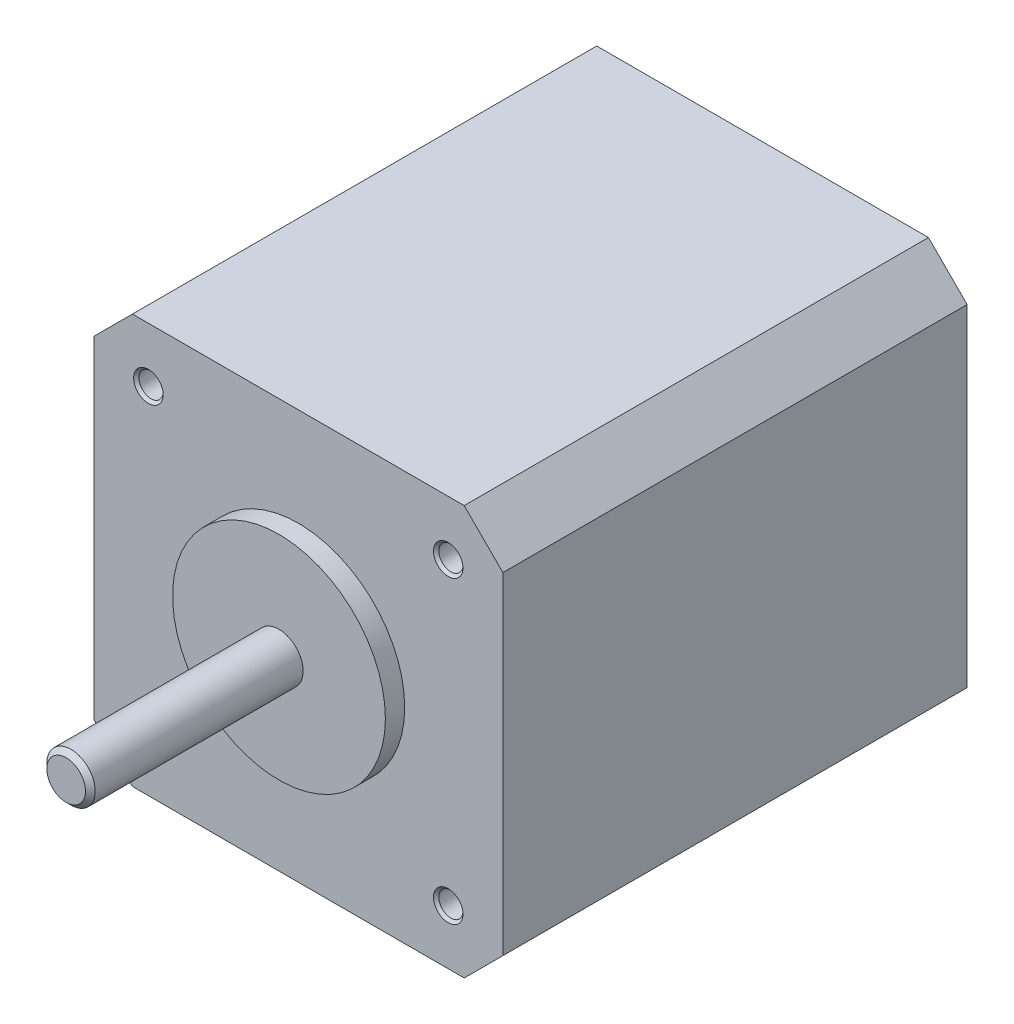
SolidWorks part; units mm, degrees
ref_plane "Front" through (0, 0, 0) normal (0, 0, 1) x (1, 0, 0)
ref_plane "Top" through (0, 0, 0) normal (0, 1, 0) x (1, 0, 0)
ref_plane "Right" through (0, 0, 0) normal (1, 0, 0) x (0, 0, -1)
sketch "Sketch1" plane through (0, 0, 0) normal (0, 0, 1) x (1, 0, 0)
  line L0 (0, 21.15) -> (0, 0) construction
  line L1 (-21.15, 21.15) -> (21.15, 21.15)
  line L2 (-21.15, 21.15) -> (-21.15, -21.15)
  line L3 (-21.15, -21.15) -> (21.15, -21.15)
  line L4 (21.15, 21.15) -> (21.15, -21.15)
  line L5 (0, 0) -> (0, -21.15) construction
  line L7 (0, 0) -> (21.15, 0) construction
  dimension "D1" = 42.3
  dimension "D2" = 42.3
extrude "Boss-Extrude1" add sketch "Sketch1" along normal blind 48
sketch "Sketch2" plane through (0, 0, 48) normal (0, 0, 1) x (1, 0, 0)
  circle A0 centre (0, 0) radius 11
  dimension "D1" = 22
extrude "Boss-Extrude2" add sketch "Sketch2" along normal blind 2
sketch "Sketch3" plane through (0, 0, 50) normal (0, 0, 1) x (1, 0, 0)
  circle A0 centre (0, 0) radius 2.5
  dimension "D1" = 5
extrude "Boss-Extrude3" add sketch "Sketch3" along normal blind 22
chamfer "Chamfer1" distance 0.5 angle 45 1 edges at (2.5, 0, 72)
chamfer "Chamfer2" distance 4 angle 45 4 edges at (-21.15, -21.15, 24) (21.15, -21.15, 24) (-21.15, 21.15, 24) (21.15, 21.15, 24)
hole_wizard "M3 Tapped Hole1" positions "3DSketch1" profile "Sketch4" tap size "M3" standard "ISO"
sketch3d "3DSketch1"
  line L0 (-15.5, -15.5, 48) -> (-15.5, -21.15, 48) construction
  line L1 (-17.15, -21.15, 48) -> (17.15, -21.15, 48) construction
  line L3 (-15.5, -15.5, 48) -> (-21.15, -15.5, 48) construction
  line L4 (-21.15, 17.15, 48) -> (-21.15, -17.15, 48) construction
  line L6 (15.5, -15.5, 48) -> (15.5, -21.15, 48) construction
  line L8 (15.5, -15.5, 48) -> (21.15, -15.5, 48) construction
  line L9 (21.15, -17.15, 48) -> (21.15, 17.15, 48) construction
  line L11 (-15.5, 15.5, 48) -> (-15.5, 21.15, 48) construction
  line L12 (17.15, 21.15, 48) -> (-17.15, 21.15, 48) construction
  line L14 (-15.5, 15.5, 48) -> (-21.15, 15.5, 48) construction
  line L16 (15.5, 15.5, 48) -> (15.5, 21.15, 48) construction
  line L18 (15.5, 15.5, 48) -> (21.15, 15.5, 48) construction
  point P0 (-15.5, 15.5, 48)
  point P2 (15.5, 15.5, 48)
  point P4 (15.5, -15.5, 48)
  point P6 (-15.5, -15.5, 48)
  dimension "D1" = 31
sketch "Sketch4" plane through (-15.5, 15.5, 48) normal (1, 0, 0) x (0, -1, 0)
  line L0 (0, 0) -> (0, 5.2511)
  line L1 (0, 5.2511) -> (1.25, 4.5)
  line L2 (1.25, 4.5) -> (1.25, 0.275)
  line L3 (1.25, 0.275) -> (1.525, 0)
  line L5 (1.525, 0) -> (0, 0)
  line L6 (-1.25, 0.275) -> (-1.525, 0) construction
  line L10 (0, 5.2511) -> (-1.25, 4.5) construction
  line L11 (0, -6.35) -> (0, 107.95) construction
  dimension "Tap Drill Dia." = 2.5
  dimension "Tap Drill Depth" = 4.5
  dimension "Near C'Sink Dia." = 3.05
  dimension "Near C'Sink Angle" = 90
  dimension "Drill Angle" = 118
sketch "Sketch5" plane through (0, -21.15, 0) normal (0, -1, 0) x (1, 0, 0)
  line L0 (-17.15, 0) -> (17.15, 0) construction
  circle A0 centre (0, 8) radius 2.5
  point P4 (0, 0)
  dimension "D1" = 5
  dimension "D2" = 8
extrude "Boss-Extrude4" add sketch "Sketch5" along normal blind 10
